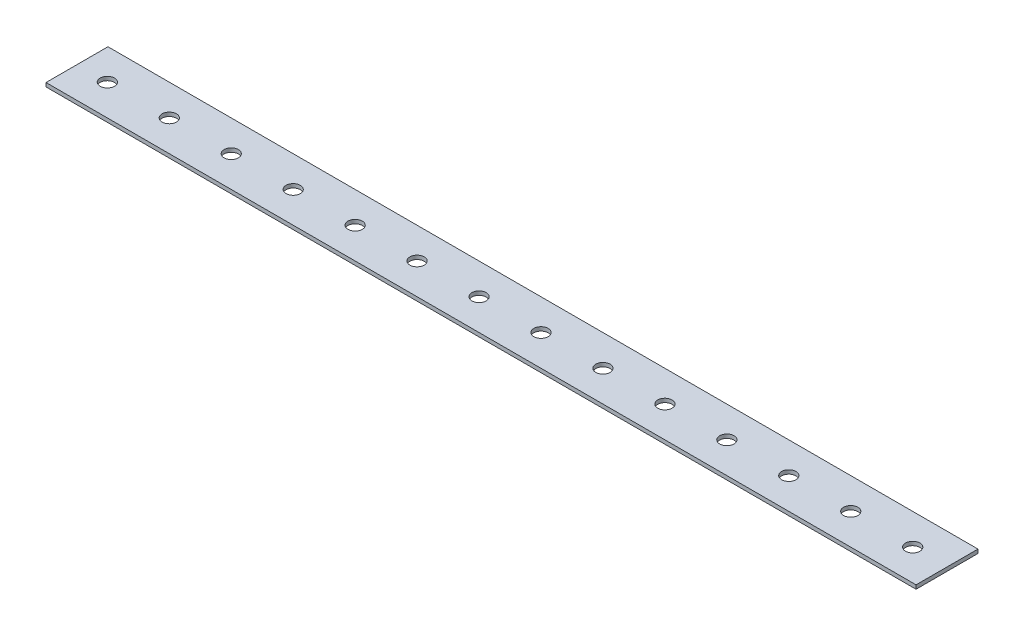
SolidWorks part; units mm, degrees
ref_plane "Front Plane" through (0, 0, 0) normal (0, 0, 1) x (1, 0, 0)
ref_plane "Top Plane" through (0, 0, 0) normal (0, 1, 0) x (1, 0, 0)
ref_plane "Right Plane" through (0, 0, 0) normal (1, 0, 0) x (0, 0, -1)
sketch "Sketch1" plane through (0, 0, 0) normal (0, 1, 0) x (1, 0, 0)
  line L0 (358.6506, -520.491) -> (1060.5272, -520.491)
  line L1 (358.6506, -520.491) -> (358.6506, -470.5142)
  line L2 (358.6506, -470.5142) -> (1060.5272, -470.5142)
  line L4 (358.6506, -495.5026) -> (1060.5272, -495.5026) construction
  line L5 (1060.5272, -470.5142) -> (1060.5272, -520.491)
  circle A0 centre (383.1436, -495.5026) radius 5.7786
  circle A1 centre (433.1203, -495.5026) radius 5.7786
  circle A2 centre (483.0971, -495.5026) radius 5.7786
  circle A3 centre (533.0738, -495.5026) radius 5.7786
  circle A4 centre (583.0506, -495.5026) radius 5.7786
  circle A5 centre (633.0273, -495.5026) radius 5.7786
  circle A6 centre (683.004, -495.5026) radius 5.7786
  circle A7 centre (732.9808, -495.5026) radius 5.7786
  circle A8 centre (782.9575, -495.5026) radius 5.7786
  circle A9 centre (832.9342, -495.5026) radius 5.7786
  circle A10 centre (882.911, -495.5026) radius 5.7786
  circle A11 centre (932.8877, -495.5026) radius 5.7786
  circle A12 centre (982.8645, -495.5026) radius 5.7786
  circle A13 centre (1032.8412, -495.5026) radius 5.7786
  dimension "D1" = 27.686
extrude "Boss-Extrude1" add sketch "Sketch1" along normal blind 3.1
